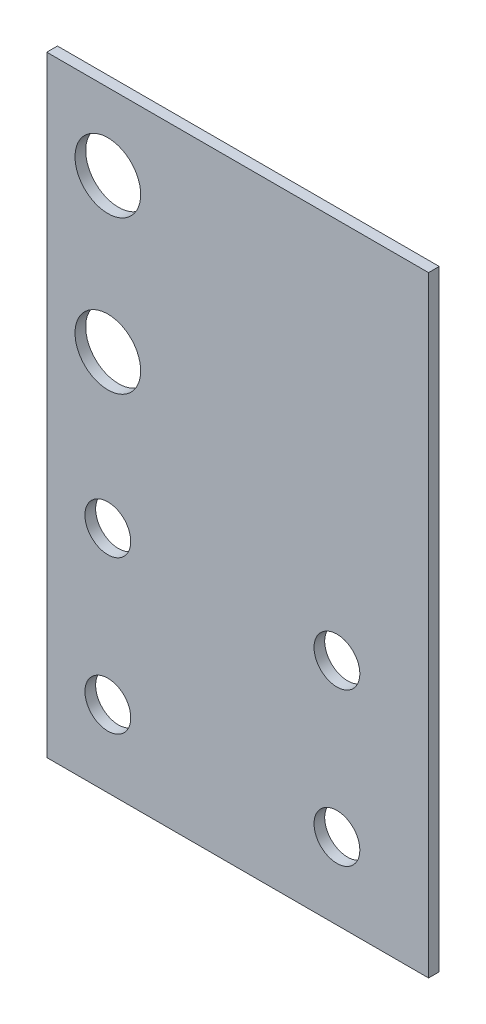
SolidWorks part; units mm, degrees
ref_plane "Front Plane" through (0, 0, 0) normal (0, 0, 1) x (1, 0, 0)
ref_plane "Top Plane" through (0, 0, 0) normal (0, 1, 0) x (1, 0, 0)
ref_plane "Right Plane" through (0, 0, 0) normal (1, 0, 0) x (0, 0, -1)
sketch "Sketch1" plane through (0, 0, 0) normal (0, 1, 0) x (1, 0, 0)
  line L1 (0, 0) -> (25, 0)
  line L2 (0, 0) -> (0, 0.7)
  line L3 (0, 0.7) -> (25, 0.7)
  line L4 (25, 0) -> (25, 0.7)
  dimension "D1" = 0.7
  dimension "D2" = 25
extrude "Boss-Extrude1" add sketch "Sketch1" along normal blind 40
sketch "Sketch2" plane through (0, 0, 0) normal (0, 0, 1) x (1, 0, 0)
  line L0 (4, 40) -> (4, 0) construction
  line L1 (0, 40) -> (25, 40) construction
  line L2 (0, 0) -> (25, 0) construction
  line L3 (19, 40) -> (19, 0) construction
  line L5 (0, 40) -> (0, 0) construction
  line L6 (19, 5) -> (4, 5) construction
  circle A0 centre (4, 35) radius 2.15
  circle A1 centre (4, 25) radius 2.15
  circle A2 centre (4, 15) radius 1.5
  circle A3 centre (4, 5) radius 1.5
  circle A4 centre (19, 15) radius 1.5
  circle A5 centre (19, 5) radius 1.5
  dimension "D7" = 4.3
  dimension "D9" = 3
  dimension "D1" = 15
  dimension "D2" = 4
  dimension "D3" = 5
  dimension "D4" = 10
  dimension "D5" = 10
  dimension "D6" = 10
  dimension "D8" = 10
extrude "Cut-Extrude1" cut sketch "Sketch2" against normal blind 40
